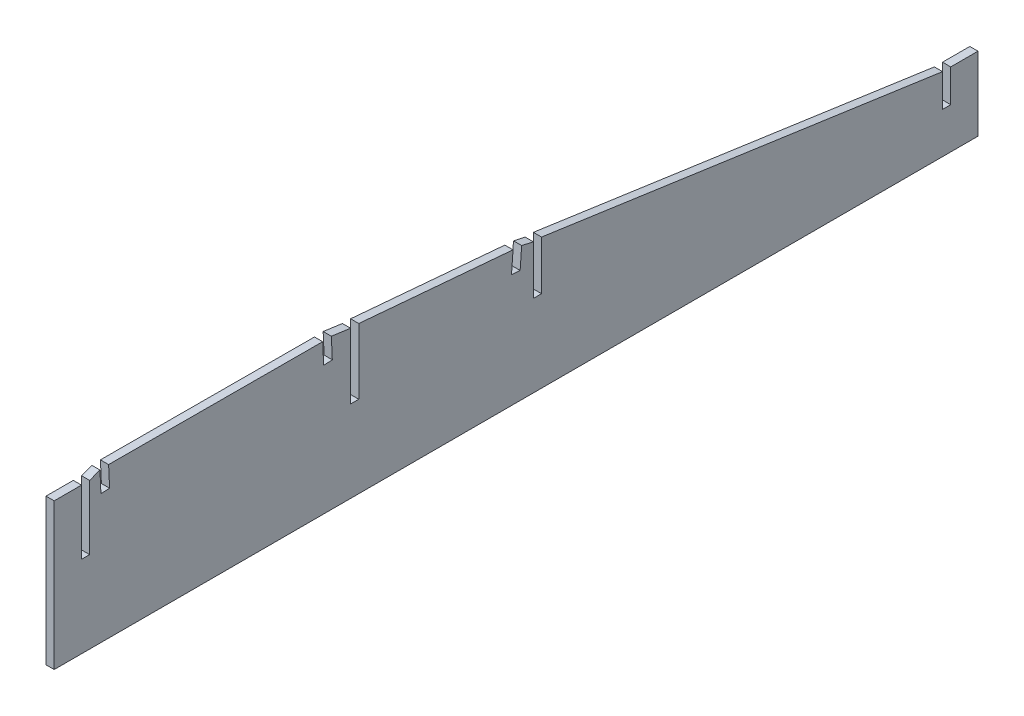
SolidWorks part; units mm, degrees
ref_plane "Front Plane" through (0, 0, 0) normal (0, 0, 1) x (1, 0, 0)
ref_plane "Top Plane" through (0, 0, 0) normal (0, 1, 0) x (1, 0, 0)
ref_plane "Right Plane" through (0, 0, 0) normal (1, 0, 0) x (0, 0, -1)
ref_plane "Plane1" through (299.875, 0, 0) normal (1, 0, 0) x (0, 0, -1)
sketch "Sketch1" plane through (299.875, 0, 0) normal (1, 0, 0) x (0, 0, -1)
  line L0 (257.343, 70.0058) -> (257.343, 46.4388)
  line L1 (257.343, 46.4388) -> (257.343, 16.4388)
  line L2 (254.343, 70.0058) -> (254.343, 46.4388)
  line L3 (254.343, 46.4388) -> (254.343, 16.4388)
  line L8 (257.343, 70.0058) -> (254.343, 70.0058)
  line L9 (254.343, 16.4388) -> (257.343, 16.4388)
  line L10 (254.343, 46.4388) -> (257.343, 46.4388)
  line L11 (254.343, 46.4388) -> (257.343, 46.4388)
  line L16 (573, 43.4436) -> (583, 43.4436)
  line L18 (583, 43.4436) -> (583, 16.4388)
  line L19 (254.343, 70.0058) -> (254.343, 46.4388)
  line L24 (583, 16.4388) -> (244.343, 16.4388)
  line L25 (257.343, 70.0058) -> (257.343, 46.4388)
  line L26 (573, 31.4436) -> (573, 16.4388)
  line L27 (573, 31.4436) -> (573, 43.4436)
  line L28 (570, 31.4436) -> (570, 16.4388)
  line L29 (570, 31.4436) -> (570, 43.4436)
  line L30 (570, 16.4388) -> (573, 16.4388)
  line L31 (570, 31.4436) -> (573, 31.4436)
  line L36 (573, 43.4436) -> (570, 43.4436)
  line L38 (570, 31.4436) -> (573, 31.4436)
  line L39 (244.343, 16.4388) -> (244.343, 70.0058)
  line L44 (570, 31.4436) -> (570, 43.4436)
  line L45 (244.343, 70.0058) -> (254.343, 70.0058)
  line L46 (573, 31.4436) -> (573, 43.4436)
  line L47 (257.343, 70.0058) -> (261.1208, 71.4044)
  line L52 (420, 46.4388) -> (420, 16.4388)
  line L53 (420, 46.4388) -> (420, 64.4234)
  line L54 (423, 46.4388) -> (423, 16.4388)
  line L55 (423, 46.4388) -> (423, 64.4234)
  line L60 (420, 64.4234) -> (423, 64.4234)
  line L61 (423, 46.4388) -> (420, 46.4388)
  line L62 (423, 16.4388) -> (420, 16.4388)
  line L63 (264.2923, 71.552) -> (342.7719, 71.322)
  line L64 (423, 46.4388) -> (420, 46.4388)
  line L66 (423, 46.4388) -> (423, 64.4234)
  line L68 (345.9435, 71.4696) -> (353, 70.4772)
  line L69 (420, 46.4388) -> (420, 64.4234)
  line L71 (356, 70.4772) -> (412.5475, 65.6008)
  line L72 (353, 70.4772) -> (353, 46.4388)
  line L73 (353, 46.4388) -> (353, 16.4388)
  line L74 (356, 70.4772) -> (356, 46.4388)
  line L75 (356, 46.4388) -> (356, 16.4388)
  line L76 (353, 70.4772) -> (356, 70.4772)
  line L77 (356, 46.4388) -> (353, 46.4388)
  line L78 (356, 16.4388) -> (353, 16.4388)
  line L79 (415.7138, 65.3656) -> (420, 64.4234)
  line L80 (356, 46.4388) -> (353, 46.4388)
  line L82 (423, 64.4234) -> (570, 43.4436)
  line L83 (356, 70.4772) -> (356, 46.4388)
  line L84 (570, 16.4388) -> (573, 16.4388) construction
  line L85 (353, 70.4772) -> (353, 46.4388)
  line L86 (261.4789, 63.7076) -> (261.1208, 71.4044)
  line L87 (264.6505, 63.8552) -> (264.2923, 71.552)
  line L88 (264.2923, 71.552) -> (261.1208, 71.4044)
  line L89 (261.4789, 63.7076) -> (264.6505, 63.8552)
  line L90 (261.4789, 63.7076) -> (264.6505, 63.8552)
  line L92 (264.6505, 63.8552) -> (264.2923, 71.552)
  line L93 (261.4789, 63.7076) -> (261.1208, 71.4044)
  line L94 (343.1289, 63.6509) -> (342.7719, 71.322)
  line L95 (346.3005, 63.7985) -> (345.9435, 71.4696)
  line L96 (343.1289, 63.6509) -> (346.3005, 63.7985)
  line L97 (345.9435, 71.4696) -> (342.7719, 71.322)
  line L99 (343.1289, 63.6509) -> (346.3005, 63.7985)
  line L100 (346.3005, 63.7985) -> (345.9435, 71.4696)
  line L101 (343.1289, 63.6509) -> (342.7719, 71.322)
  line L102 (411.9815, 57.9791) -> (412.5475, 65.6008)
  line L103 (415.1477, 57.7439) -> (415.7138, 65.3656)
  line L104 (412.5475, 65.6008) -> (415.7138, 65.3656)
  line L105 (415.1477, 57.7439) -> (411.9815, 57.9791)
  line L106 (415.1477, 57.7439) -> (411.9815, 57.9791)
  line L108 (415.1477, 57.7439) -> (415.7138, 65.3656)
  line L109 (411.9815, 57.9791) -> (412.5475, 65.6008)
  dimension "D1" = 10
  dimension "D2" = 10
extrude "Boss-Extrude1" add sketch "Sketch1" against normal blind 3
